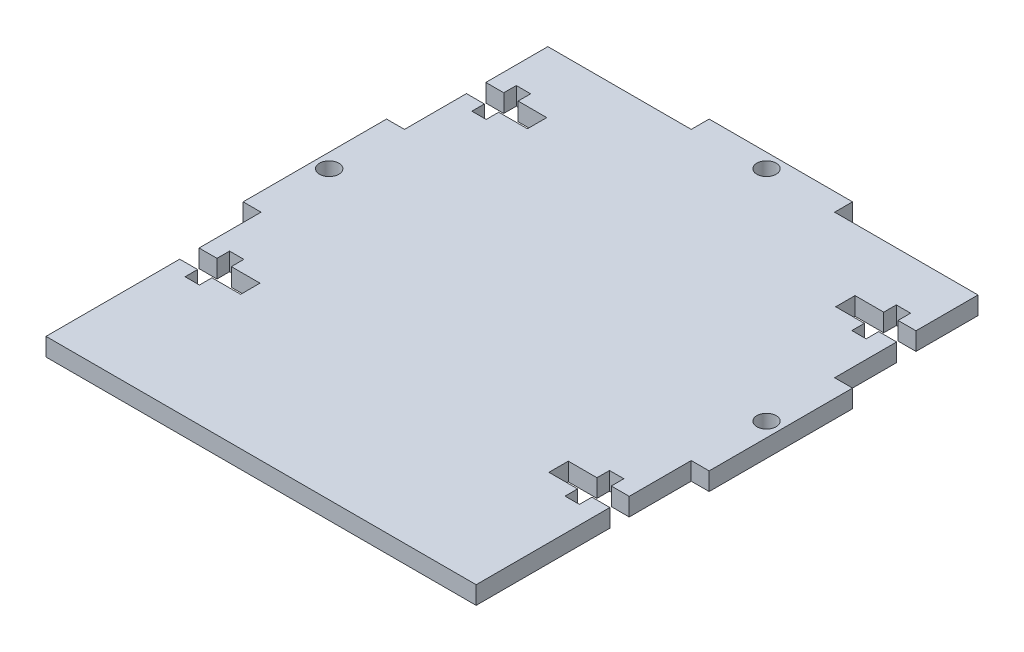
SolidWorks part; units mm, degrees
ref_plane "Front Plane" through (0, 0, 0) normal (0, 0, 1) x (1, 0, 0)
ref_plane "Top Plane" through (0, 0, 0) normal (0, 1, 0) x (1, 0, 0)
ref_plane "Right Plane" through (0, 0, 0) normal (1, 0, 0) x (0, 0, -1)
sketch "Sketch1" plane through (0, 0, 0) normal (0, 1, 0) x (1, 0, 0)
  line L0 (-38.1, 0) -> (-38.1, 23.6855)
  line L1 (-38.1, 38.1) -> (-41.275, 38.1)
  line L2 (-41.275, 38.1) -> (-41.275, 63.5)
  line L3 (-41.275, 63.5) -> (-38.1, 63.5)
  line L4 (-38.1, 63.5) -> (-38.1, 74.4855)
  line L5 (-38.1, 88.9) -> (-12.7, 88.9)
  line L6 (-12.7, 88.9) -> (-12.7, 92.075)
  line L7 (-12.7, 92.075) -> (12.7, 92.075)
  line L8 (0, 0) -> (0, 92.075) construction
  line L9 (-38.1, 0) -> (38.1, 0)
  line L10 (-38.1, 76.2) -> (-24.0005, 76.2) construction
  line L11 (-38.1, 25.4) -> (-27.0779, 25.4) construction
  line L12 (-41.275, 50.8) -> (-26.3932, 50.8) construction
  line L13 (-38.1, 77.9145) -> (-34.925, 77.9145)
  line L14 (-34.925, 77.9145) -> (-34.925, 80.137)
  line L15 (-34.925, 80.137) -> (-32.385, 80.137)
  line L16 (-32.385, 80.137) -> (-32.385, 77.9145)
  line L17 (-32.385, 77.9145) -> (-27.305, 77.9145)
  line L18 (-27.305, 77.9145) -> (-27.305, 74.4855)
  line L19 (-32.385, 74.4855) -> (-27.305, 74.4855)
  line L20 (-32.385, 72.263) -> (-32.385, 74.4855)
  line L21 (-34.925, 72.263) -> (-32.385, 72.263)
  line L22 (-34.925, 74.4855) -> (-34.925, 72.263)
  line L23 (-38.1, 74.4855) -> (-34.925, 74.4855)
  line L24 (-38.1, 77.9145) -> (-38.1, 88.9)
  line L25 (-38.1, 74.4855) -> (-38.1, 63.5)
  line L26 (-38.1, 77.9145) -> (-34.925, 77.9145)
  line L27 (-34.925, 77.9145) -> (-34.925, 80.137)
  line L28 (-34.925, 80.137) -> (-32.385, 80.137)
  line L29 (-32.385, 80.137) -> (-32.385, 77.9145)
  line L30 (-32.385, 77.9145) -> (-27.305, 77.9145)
  line L31 (-32.385, 74.4855) -> (-27.305, 74.4855)
  line L32 (-32.385, 72.263) -> (-32.385, 74.4855)
  line L33 (-34.925, 72.263) -> (-32.385, 72.263)
  line L34 (-34.925, 74.4855) -> (-34.925, 72.263)
  line L35 (-38.1, 74.4855) -> (-34.925, 74.4855)
  line L36 (-38.1, 88.9) -> (-38.1, 77.9145)
  line L37 (-38.1, 77.9145) -> (-34.925, 77.9145)
  line L38 (-34.925, 77.9145) -> (-34.925, 80.137)
  line L39 (-34.925, 80.137) -> (-32.385, 80.137)
  line L40 (-32.385, 80.137) -> (-32.385, 77.9145)
  line L41 (-32.385, 77.9145) -> (-27.305, 77.9145)
  line L42 (-32.385, 74.4855) -> (-27.305, 74.4855)
  line L43 (-32.385, 72.263) -> (-32.385, 74.4855)
  line L44 (-34.925, 72.263) -> (-32.385, 72.263)
  line L45 (-34.925, 74.4855) -> (-34.925, 72.263)
  line L46 (-38.1, 74.4855) -> (-34.925, 74.4855)
  line L47 (-38.1, 77.9145) -> (-34.925, 77.9145)
  line L48 (-34.925, 77.9145) -> (-34.925, 80.137)
  line L49 (-34.925, 80.137) -> (-32.385, 80.137)
  line L50 (-32.385, 80.137) -> (-32.385, 77.9145)
  line L51 (-32.385, 77.9145) -> (-27.305, 77.9145)
  line L52 (-32.385, 74.4855) -> (-27.305, 74.4855)
  line L53 (-32.385, 72.263) -> (-32.385, 74.4855)
  line L54 (-34.925, 72.263) -> (-32.385, 72.263)
  line L55 (-34.925, 74.4855) -> (-34.925, 72.263)
  line L56 (-38.1, 74.4855) -> (-34.925, 74.4855)
  line L58 (-38.1, 27.1145) -> (-34.925, 27.1145)
  line L59 (-34.925, 27.1145) -> (-34.925, 29.337)
  line L60 (-34.925, 29.337) -> (-32.385, 29.337)
  line L61 (-32.385, 29.337) -> (-32.385, 27.1145)
  line L62 (-32.385, 27.1145) -> (-27.305, 27.1145)
  line L63 (-32.385, 23.6855) -> (-27.305, 23.6855)
  line L64 (-32.385, 21.463) -> (-32.385, 23.6855)
  line L65 (-34.925, 21.463) -> (-32.385, 21.463)
  line L66 (-34.925, 23.6855) -> (-34.925, 21.463)
  line L67 (-38.1, 23.6855) -> (-34.925, 23.6855)
  line L68 (-38.1, 27.1145) -> (-34.925, 27.1145)
  line L69 (-34.925, 27.1145) -> (-34.925, 29.337)
  line L70 (-34.925, 29.337) -> (-32.385, 29.337)
  line L71 (-32.385, 29.337) -> (-32.385, 27.1145)
  line L72 (-32.385, 27.1145) -> (-27.305, 27.1145)
  line L73 (-32.385, 23.6855) -> (-27.305, 23.6855)
  line L74 (-32.385, 21.463) -> (-32.385, 23.6855)
  line L75 (-34.925, 21.463) -> (-32.385, 21.463)
  line L76 (-34.925, 23.6855) -> (-34.925, 21.463)
  line L77 (-38.1, 23.6855) -> (-34.925, 23.6855)
  line L78 (-38.1, 27.1145) -> (-34.925, 27.1145)
  line L79 (-34.925, 27.1145) -> (-34.925, 29.337)
  line L80 (-34.925, 29.337) -> (-32.385, 29.337)
  line L81 (-32.385, 29.337) -> (-32.385, 27.1145)
  line L82 (-32.385, 27.1145) -> (-27.305, 27.1145)
  line L83 (-32.385, 23.6855) -> (-27.305, 23.6855)
  line L84 (-32.385, 21.463) -> (-32.385, 23.6855)
  line L85 (-34.925, 21.463) -> (-32.385, 21.463)
  line L86 (-34.925, 23.6855) -> (-34.925, 21.463)
  line L87 (-38.1, 23.6855) -> (-34.925, 23.6855)
  line L88 (-38.1, 27.1145) -> (-34.925, 27.1145)
  line L89 (-34.925, 27.1145) -> (-34.925, 29.337)
  line L90 (-34.925, 29.337) -> (-32.385, 29.337)
  line L91 (-32.385, 29.337) -> (-32.385, 27.1145)
  line L92 (-32.385, 27.1145) -> (-27.305, 27.1145)
  line L93 (-27.305, 23.6855) -> (-27.305, 27.1145)
  line L94 (-32.385, 23.6855) -> (-27.305, 23.6855)
  line L95 (-32.385, 21.463) -> (-32.385, 23.6855)
  line L96 (-34.925, 21.463) -> (-32.385, 21.463)
  line L97 (-34.925, 23.6855) -> (-34.925, 21.463)
  line L98 (-38.1, 23.6855) -> (-34.925, 23.6855)
  line L99 (-38.1, 27.1145) -> (-38.1, 38.1)
  line L100 (38.1, 25.4) -> (24.0005, 25.4) construction
  line L101 (41.275, 50.8) -> (26.3932, 50.8) construction
  line L102 (38.1, 25.4) -> (27.0779, 25.4) construction
  line L103 (38.1, 76.2) -> (24.0005, 76.2) construction
  line L104 (38.1, 27.1145) -> (38.1, 38.1)
  line L105 (38.1, 23.6855) -> (34.925, 23.6855)
  line L106 (34.925, 23.6855) -> (34.925, 21.463)
  line L107 (34.925, 21.463) -> (32.385, 21.463)
  line L108 (32.385, 21.463) -> (32.385, 23.6855)
  line L109 (32.385, 23.6855) -> (27.305, 23.6855)
  line L110 (27.305, 23.6855) -> (27.305, 27.1145)
  line L111 (32.385, 27.1145) -> (27.305, 27.1145)
  line L112 (32.385, 29.337) -> (32.385, 27.1145)
  line L113 (34.925, 29.337) -> (32.385, 29.337)
  line L114 (34.925, 27.1145) -> (34.925, 29.337)
  line L115 (38.1, 27.1145) -> (34.925, 27.1145)
  line L116 (38.1, 23.6855) -> (34.925, 23.6855)
  line L117 (34.925, 23.6855) -> (34.925, 21.463)
  line L118 (34.925, 21.463) -> (32.385, 21.463)
  line L119 (32.385, 21.463) -> (32.385, 23.6855)
  line L120 (32.385, 23.6855) -> (27.305, 23.6855)
  line L121 (32.385, 27.1145) -> (27.305, 27.1145)
  line L122 (32.385, 29.337) -> (32.385, 27.1145)
  line L123 (34.925, 29.337) -> (32.385, 29.337)
  line L124 (34.925, 27.1145) -> (34.925, 29.337)
  line L125 (38.1, 27.1145) -> (34.925, 27.1145)
  line L126 (38.1, 23.6855) -> (34.925, 23.6855)
  line L127 (34.925, 23.6855) -> (34.925, 21.463)
  line L128 (34.925, 21.463) -> (32.385, 21.463)
  line L129 (32.385, 21.463) -> (32.385, 23.6855)
  line L130 (32.385, 23.6855) -> (27.305, 23.6855)
  line L131 (32.385, 27.1145) -> (27.305, 27.1145)
  line L132 (32.385, 29.337) -> (32.385, 27.1145)
  line L133 (34.925, 29.337) -> (32.385, 29.337)
  line L134 (34.925, 27.1145) -> (34.925, 29.337)
  line L135 (38.1, 27.1145) -> (34.925, 27.1145)
  line L136 (38.1, 23.6855) -> (34.925, 23.6855)
  line L137 (34.925, 23.6855) -> (34.925, 21.463)
  line L138 (34.925, 21.463) -> (32.385, 21.463)
  line L139 (32.385, 21.463) -> (32.385, 23.6855)
  line L140 (32.385, 23.6855) -> (27.305, 23.6855)
  line L141 (32.385, 27.1145) -> (27.305, 27.1145)
  line L142 (32.385, 29.337) -> (32.385, 27.1145)
  line L143 (34.925, 29.337) -> (32.385, 29.337)
  line L144 (34.925, 27.1145) -> (34.925, 29.337)
  line L145 (38.1, 27.1145) -> (34.925, 27.1145)
  line L146 (38.1, 74.4855) -> (34.925, 74.4855)
  line L147 (34.925, 74.4855) -> (34.925, 72.263)
  line L148 (34.925, 72.263) -> (32.385, 72.263)
  line L149 (32.385, 72.263) -> (32.385, 74.4855)
  line L150 (32.385, 74.4855) -> (27.305, 74.4855)
  line L151 (32.385, 77.9145) -> (27.305, 77.9145)
  line L152 (32.385, 80.137) -> (32.385, 77.9145)
  line L153 (34.925, 80.137) -> (32.385, 80.137)
  line L154 (34.925, 77.9145) -> (34.925, 80.137)
  line L155 (38.1, 77.9145) -> (34.925, 77.9145)
  line L156 (38.1, 74.4855) -> (34.925, 74.4855)
  line L157 (34.925, 74.4855) -> (34.925, 72.263)
  line L158 (34.925, 72.263) -> (32.385, 72.263)
  line L159 (32.385, 72.263) -> (32.385, 74.4855)
  line L160 (32.385, 74.4855) -> (27.305, 74.4855)
  line L161 (32.385, 77.9145) -> (27.305, 77.9145)
  line L162 (32.385, 80.137) -> (32.385, 77.9145)
  line L163 (34.925, 80.137) -> (32.385, 80.137)
  line L164 (34.925, 77.9145) -> (34.925, 80.137)
  line L165 (38.1, 77.9145) -> (34.925, 77.9145)
  line L166 (38.1, 88.9) -> (38.1, 77.9145)
  line L167 (38.1, 74.4855) -> (34.925, 74.4855)
  line L168 (34.925, 74.4855) -> (34.925, 72.263)
  line L169 (34.925, 72.263) -> (32.385, 72.263)
  line L170 (32.385, 72.263) -> (32.385, 74.4855)
  line L171 (32.385, 74.4855) -> (27.305, 74.4855)
  line L172 (32.385, 77.9145) -> (27.305, 77.9145)
  line L173 (32.385, 80.137) -> (32.385, 77.9145)
  line L174 (34.925, 80.137) -> (32.385, 80.137)
  line L175 (34.925, 77.9145) -> (34.925, 80.137)
  line L176 (38.1, 77.9145) -> (34.925, 77.9145)
  line L177 (38.1, 74.4855) -> (38.1, 63.5)
  line L178 (38.1, 77.9145) -> (38.1, 88.9)
  line L179 (38.1, 74.4855) -> (34.925, 74.4855)
  line L180 (34.925, 74.4855) -> (34.925, 72.263)
  line L181 (34.925, 72.263) -> (32.385, 72.263)
  line L182 (32.385, 72.263) -> (32.385, 74.4855)
  line L183 (32.385, 74.4855) -> (27.305, 74.4855)
  line L184 (27.305, 77.9145) -> (27.305, 74.4855)
  line L185 (32.385, 77.9145) -> (27.305, 77.9145)
  line L186 (32.385, 80.137) -> (32.385, 77.9145)
  line L187 (34.925, 80.137) -> (32.385, 80.137)
  line L188 (34.925, 77.9145) -> (34.925, 80.137)
  line L189 (38.1, 77.9145) -> (34.925, 77.9145)
  line L190 (12.7, 88.9) -> (12.7, 92.075)
  line L191 (38.1, 88.9) -> (12.7, 88.9)
  line L192 (38.1, 63.5) -> (38.1, 74.4855)
  line L193 (41.275, 63.5) -> (38.1, 63.5)
  line L194 (41.275, 38.1) -> (41.275, 63.5)
  line L195 (38.1, 38.1) -> (41.275, 38.1)
  line L196 (38.1, 0) -> (38.1, 23.6855)
  circle A0 centre (-38.735, 50.8) radius 1.7145
  circle A1 centre (0, 89.535) radius 1.7145
  circle A2 centre (38.735, 50.8) radius 1.7145
  point P26 (-27.305, 76.2)
  point P43 (-27.305, 25.4)
  point P89 (27.305, 25.4)
  point P90 (27.305, 76.2)
  dimension "D12" = 3.429
  dimension "D15" = 3.429
  dimension "D2" = 12.7
  dimension "D3" = 25.4
  dimension "D4" = 3.175
  dimension "D5" = 1.7145
  dimension "D6" = 3.937
  dimension "D7" = 3.175
  dimension "D8" = 2.54
  dimension "D9" = 13.97
  dimension "D10" = 38.1
  dimension "D11" = 3.175
  dimension "D13" = 2.54
  dimension "D14" = 12.7
  dimension "D16" = 2.54
extrude "Boss-Extrude1" add sketch "Sketch1" along normal blind 3.175 contours L9 L196 L105 L106 L107 L108 L109 L110 L111 L112 L113 L114 L115 L104 L195 L194 L193 L177 L146 L147 L148 L149 L150 L184 L151 L152 L153 L154 L155 L166 L191 L190 L7 L6 L5 L24 L13 L14 L15 L16 L17 L18 L19 L20 L21 L22 L23 L4 L3 L2 L1
